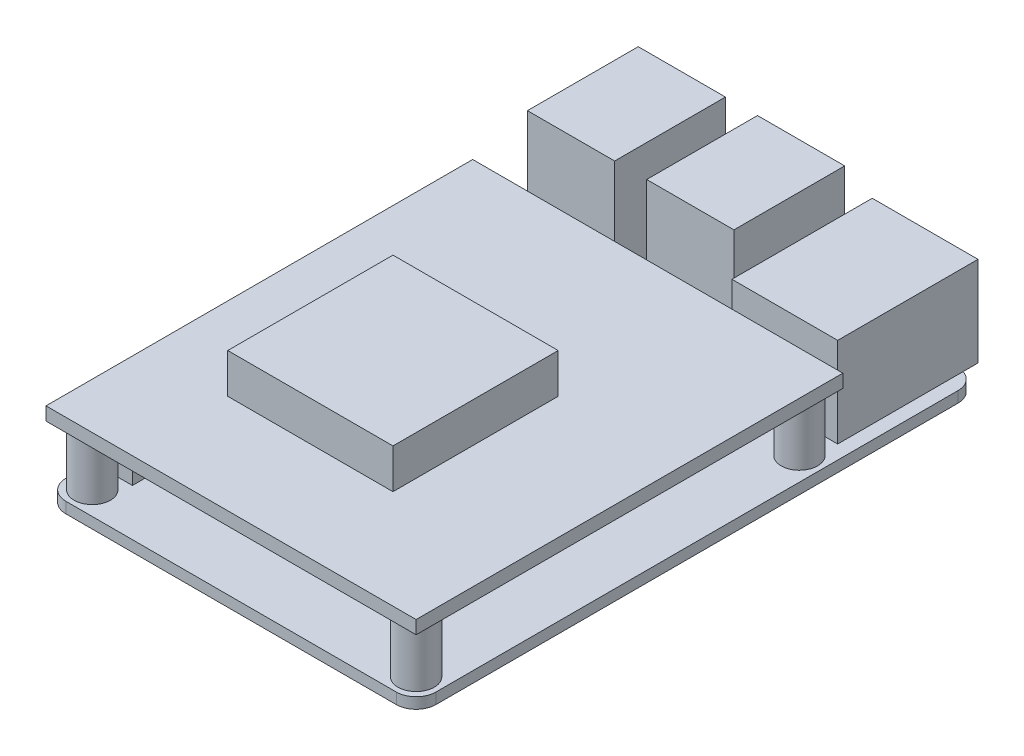
SolidWorks part; units mm, degrees
ref_plane "Front Plane" through (0, 0, 0) normal (0, 0, 1) x (1, 0, 0)
ref_plane "Top Plane" through (0, 0, 0) normal (0, 1, 0) x (1, 0, 0)
ref_plane "Right Plane" through (0, 0, 0) normal (1, 0, 0) x (0, 0, -1)
sketch "Sketch1" plane through (0, 0, 0) normal (0, 1, 0) x (1, 0, 0)
  line L5 (0, -10) -> (0, 0) construction
  line L7 (-24.5, -39) -> (24.5, -39) construction
  line L8 (-24.5, -39) -> (-24.5, 19) construction
  line L13 (-24.5, 19) -> (24.5, 19) construction
  line L14 (24.5, -39) -> (24.5, 19) construction
  line L15 (-24.5, -39) -> (24.5, 19) construction
  line L22 (-24.5, 19) -> (24.5, -39) construction
  line L23 (-25, -42.5) -> (25, -42.5)
  line L24 (-28, -39.5) -> (-28, 39.5)
  line L25 (-25, 42.5) -> (25, 42.5)
  line L26 (28, -39.5) -> (28, 39.5)
  line L27 (-28, -42.5) -> (28, 42.5) construction
  line L28 (-28, 42.5) -> (28, -42.5) construction
  line L29 (28, 0) -> (-28, 0) construction
  circle A22 centre (24.5, 19) radius 1.75
  circle A23 centre (-24.5, 19) radius 1.75
  circle A24 centre (-24.5, -39) radius 1.75
  circle A25 centre (24.5, -39) radius 1.75
  arc A26 (25, -42.5) -> (28, -39.5) centre (25, -39.5) ccw
  arc A27 (-25, -42.5) -> (-28, -39.5) centre (-25, -39.5) cw
  arc A28 (-28, 39.5) -> (-25, 42.5) centre (-25, 39.5) cw
  arc A29 (25, 42.5) -> (28, 39.5) centre (25, 39.5) cw
  point P2 (0, -10)
  point P14 (0, 0)
  dimension "D1" = 3.5
  dimension "D5" = 3
  dimension "D6" = 85
  dimension "D8" = 23.5
  dimension "D3" = 58
  dimension "D4" = 49
  dimension "D7" = 56
extrude "Boss-Extrude1" add sketch "Sketch1" along normal blind 1.651
sketch "Sketch2" plane through (0, 1.651, 0) normal (0, 1, 0) x (1, 0, 0)
  line L0 (-25.5108, 36.2389) -> (5.7312, 36.2389) construction
  line L1 (-25.5108, 44.6209) -> (-12.3155, 44.6209)
  line L2 (-25.5108, 44.6209) -> (-25.5108, 27.8569)
  line L3 (-25.5108, 27.8569) -> (-12.3155, 27.8569)
  line L4 (-12.3155, 44.6209) -> (-12.3155, 27.8569)
  line L5 (-7.4641, 44.6209) -> (5.7312, 44.6209)
  line L6 (-7.4641, 44.6209) -> (-7.4641, 27.8569)
  line L7 (-7.4641, 27.8569) -> (5.7312, 27.8569)
  line L8 (5.7312, 44.6209) -> (5.7312, 27.8569)
  line L9 (-28, 39.5) -> (-28, -39.5) construction
  line L11 (25, 42.5) -> (-25, 42.5) construction
  dimension "D1" = 13.1953
  dimension "D2" = 16.764
  dimension "D3" = 4.8514
  dimension "D4" = 2.4892
  dimension "D5" = 2.1209
extrude "Boss-Extrude2" add sketch "Sketch2" along normal blind 15.748
sketch "Sketch4" plane through (0, 1.651, 0) normal (0, 1, 0) x (1, 0, 0)
  line L0 (5.7312, 44.6209) -> (-7.4641, 44.6209) construction
  line L1 (9.8968, 44.6209) -> (25.8988, 44.6209)
  line L2 (9.8968, 44.6209) -> (9.8968, 23.389)
  line L3 (9.8968, 23.389) -> (25.8988, 23.389)
  line L4 (25.8988, 44.6209) -> (25.8988, 23.389)
  line L5 (5.7312, 27.8569) -> (5.7312, 44.6209) construction
  dimension "D1" = 16.002
  dimension "D2" = 21.2319
  dimension "D3" = 4.1656
extrude "Boss-Extrude3" add sketch "Sketch4" along normal blind 13.589
sketch "Sketch3" plane through (0, 0, -44.6209) normal (0, 0, -1) x (-1, 0, 0)
  line L0 (12.3155, 1.651) -> (25.5108, 1.651) construction
  line L1 (25.5108, 1.651) -> (25.5108, 17.399) construction
  line L2 (25.5108, 17.399) -> (12.3155, 17.399) construction
  line L3 (12.3155, 17.399) -> (12.3155, 1.651) construction
  line L4 (-5.7312, 1.651) -> (7.4641, 1.651) construction
  line L5 (7.4641, 1.651) -> (7.4641, 17.399) construction
  line L6 (7.4641, 17.399) -> (-5.7312, 17.399) construction
  line L7 (-5.7312, 17.399) -> (-5.7312, 1.651) construction
  line L8 (12.3155, 1.651) -> (25.5108, 1.651) construction
  line L9 (25.5108, 1.651) -> (25.5108, 17.399) construction
  line L10 (25.5108, 17.399) -> (12.3155, 17.399) construction
  line L11 (12.3155, 17.399) -> (12.3155, 1.651) construction
  line L12 (-5.7312, 1.651) -> (7.4641, 1.651) construction
  line L13 (7.4641, 1.651) -> (7.4641, 17.399) construction
  line L14 (7.4641, 17.399) -> (-5.7312, 17.399) construction
  line L15 (-5.7312, 17.399) -> (-5.7312, 1.651) construction
  line L16 (13.5855, 2.921) -> (24.2408, 2.921)
  line L17 (24.2408, 2.921) -> (24.2408, 8.89)
  line L18 (24.2408, 16.129) -> (13.5855, 16.129)
  line L19 (13.5855, 16.129) -> (13.5855, 10.16)
  line L20 (-4.4612, 2.921) -> (6.1941, 2.921)
  line L21 (6.1941, 2.921) -> (6.1941, 8.89)
  line L22 (6.1941, 16.129) -> (-4.4612, 16.129)
  line L23 (-4.4612, 16.129) -> (-4.4612, 10.16)
  line L24 (-24.6288, 2.921) -> (-11.1668, 2.921)
  line L25 (-11.1668, 2.921) -> (-11.1668, 13.97)
  line L26 (-11.1668, 13.97) -> (-24.6288, 13.97)
  line L27 (-24.6288, 13.97) -> (-24.6288, 2.921)
  line L28 (-25.8988, 1.651) -> (-9.8968, 1.651)
  line L29 (-9.8968, 1.651) -> (-9.8968, 15.24)
  line L30 (-9.8968, 15.24) -> (-25.8988, 15.24)
  line L31 (-25.8988, 15.24) -> (-25.8988, 1.651)
  line L32 (-25.8988, 1.651) -> (-9.8968, 1.651) construction
  line L33 (-9.8968, 1.651) -> (-9.8968, 15.24) construction
  line L34 (-9.8968, 15.24) -> (-25.8988, 15.24) construction
  line L35 (-25.8988, 15.24) -> (-25.8988, 1.651) construction
  line L36 (-4.4612, 9.525) -> (6.1941, 9.525) construction
  line L37 (13.5855, 9.525) -> (24.2408, 9.525) construction
  line L38 (-4.4612, 8.89) -> (6.1941, 8.89)
  line L39 (13.5855, 8.89) -> (24.2408, 8.89)
  line L40 (-4.4612, 10.16) -> (6.1941, 10.16)
  line L41 (13.5855, 10.16) -> (24.2408, 10.16)
  line L42 (13.5855, 8.89) -> (13.5855, 2.921)
  line L43 (13.5855, 16.129) -> (13.5855, 2.921) construction
  line L44 (24.2408, 10.16) -> (24.2408, 16.129)
  line L45 (24.2408, 2.921) -> (24.2408, 16.129) construction
  line L46 (6.1941, 10.16) -> (6.1941, 16.129)
  line L47 (6.1941, 2.921) -> (6.1941, 16.129) construction
  line L48 (-4.4612, 8.89) -> (-4.4612, 2.921)
  line L49 (-4.4612, 16.129) -> (-4.4612, 2.921) construction
  dimension "D1" = 1.27
  dimension "D2" = 0
  dimension "D3" = 1.27
  dimension "D4" = 0.635
  dimension "D5" = 0.635
extrude "Cut-Extrude1" cut sketch "Sketch3" against normal blind 15.748
sketch "Sketch5" plane through (0, 1.651, 0) normal (0, 1, 0) x (1, 0, 0)
  line L0 (-24.5, 19) -> (-24.5, 15.4) construction
  line L1 (-26.9765, 15.4) -> (-22.0235, 15.4)
  line L2 (-26.9765, 15.4) -> (-26.9765, -35.4)
  line L3 (-26.9765, -35.4) -> (-22.0235, -35.4)
  line L4 (-22.0235, 15.4) -> (-22.0235, -35.4)
  line L5 (-24.5, -39) -> (-24.5, -35.4) construction
  dimension "D1" = 50.8
  dimension "D2" = 4.953
extrude "Boss-Extrude4" add sketch "Sketch5" along normal blind 2.4892
sketch "Sketch6" plane through (0, 4.1402, 0) normal (0, 1, 0) x (1, 0, 0)
  line L0 (-25.8081, 13.9077) -> (-23.1919, 13.9077) construction
  line L3 (-24.5, 15.4) -> (-24.5, -35.4) construction
  line L4 (-26.1065, 13.6093) -> (-25.5096, 13.6093)
  line L5 (-26.1065, 13.6093) -> (-26.1065, 14.2062)
  line L6 (-26.1065, 14.2062) -> (-25.5096, 14.2062)
  line L7 (-25.5096, 13.6093) -> (-25.5096, 14.2062)
  line L8 (-26.1065, 13.6093) -> (-25.5096, 14.2062) construction
  line L9 (-26.1065, 14.2062) -> (-25.5096, 13.6093) construction
  line L10 (-23.4903, 13.6093) -> (-22.8934, 13.6093)
  line L11 (-23.4903, 13.6093) -> (-23.4903, 14.2062)
  line L12 (-23.4903, 14.2062) -> (-22.8934, 14.2062)
  line L13 (-22.8934, 13.6093) -> (-22.8934, 14.2062)
  line L14 (-23.4903, 13.6093) -> (-22.8934, 14.2062) construction
  line L15 (-23.4903, 14.2062) -> (-22.8934, 13.6093) construction
  line L16 (-22.0235, 15.4) -> (-26.9765, 15.4) construction
  line L17 (-26.9765, -35.4) -> (-22.0235, -35.4) construction
  line L18 (-26.1065, 11.0693) -> (-25.5096, 11.0693)
  line L19 (-26.1065, 11.0693) -> (-26.1065, 11.6662)
  line L20 (-25.5096, 11.0693) -> (-25.5096, 11.6662)
  line L21 (-26.1065, 11.6662) -> (-25.5096, 11.6662)
  line L22 (-25.8081, 11.3677) -> (-23.1919, 11.3677) construction
  line L23 (-23.4903, 11.0693) -> (-23.4903, 11.6662)
  line L24 (-23.4903, 11.6662) -> (-22.8934, 11.6662)
  line L25 (-22.8934, 11.0693) -> (-22.8934, 11.6662)
  line L26 (-23.4903, 11.0693) -> (-22.8934, 11.0693)
  line L27 (-26.1065, 8.5293) -> (-25.5096, 8.5293)
  line L28 (-26.1065, 8.5293) -> (-26.1065, 9.1262)
  line L29 (-25.5096, 8.5293) -> (-25.5096, 9.1262)
  line L30 (-26.1065, 9.1262) -> (-25.5096, 9.1262)
  line L31 (-25.8081, 8.8277) -> (-23.1919, 8.8277) construction
  line L32 (-23.4903, 8.5293) -> (-23.4903, 9.1262)
  line L33 (-23.4903, 9.1262) -> (-22.8934, 9.1262)
  line L34 (-22.8934, 8.5293) -> (-22.8934, 9.1262)
  line L35 (-23.4903, 8.5293) -> (-22.8934, 8.5293)
  line L36 (-26.1065, 5.9893) -> (-25.5096, 5.9893)
  line L37 (-26.1065, 5.9893) -> (-26.1065, 6.5862)
  line L38 (-25.5096, 5.9893) -> (-25.5096, 6.5862)
  line L39 (-26.1065, 6.5862) -> (-25.5096, 6.5862)
  line L40 (-25.8081, 6.2877) -> (-23.1919, 6.2877) construction
  line L41 (-23.4903, 5.9893) -> (-23.4903, 6.5862)
  line L42 (-23.4903, 6.5862) -> (-22.8934, 6.5862)
  line L43 (-22.8934, 5.9893) -> (-22.8934, 6.5862)
  line L44 (-23.4903, 5.9893) -> (-22.8934, 5.9893)
  line L45 (-26.1065, 3.4493) -> (-25.5096, 3.4493)
  line L46 (-26.1065, 3.4493) -> (-26.1065, 4.0462)
  line L47 (-25.5096, 3.4493) -> (-25.5096, 4.0462)
  line L48 (-26.1065, 4.0462) -> (-25.5096, 4.0462)
  line L49 (-25.8081, 3.7477) -> (-23.1919, 3.7477) construction
  line L50 (-23.4903, 3.4493) -> (-23.4903, 4.0462)
  line L51 (-23.4903, 4.0462) -> (-22.8934, 4.0462)
  line L52 (-22.8934, 3.4493) -> (-22.8934, 4.0462)
  line L53 (-23.4903, 3.4493) -> (-22.8934, 3.4493)
  line L54 (-26.1065, 0.9093) -> (-25.5096, 0.9093)
  line L55 (-26.1065, 0.9093) -> (-26.1065, 1.5062)
  line L56 (-25.5096, 0.9093) -> (-25.5096, 1.5062)
  line L57 (-26.1065, 1.5062) -> (-25.5096, 1.5062)
  line L58 (-25.8081, 1.2077) -> (-23.1919, 1.2077) construction
  line L59 (-23.4903, 0.9093) -> (-23.4903, 1.5062)
  line L60 (-23.4903, 1.5062) -> (-22.8934, 1.5062)
  line L61 (-22.8934, 0.9093) -> (-22.8934, 1.5062)
  line L62 (-23.4903, 0.9093) -> (-22.8934, 0.9093)
  line L63 (-26.1065, -1.6307) -> (-25.5096, -1.6307)
  line L64 (-26.1065, -1.6307) -> (-26.1065, -1.0338)
  line L65 (-25.5096, -1.6307) -> (-25.5096, -1.0338)
  line L66 (-26.1065, -1.0338) -> (-25.5096, -1.0338)
  line L67 (-25.8081, -1.3323) -> (-23.1919, -1.3323) construction
  line L68 (-23.4903, -1.6307) -> (-23.4903, -1.0338)
  line L69 (-23.4903, -1.0338) -> (-22.8934, -1.0338)
  line L70 (-22.8934, -1.6307) -> (-22.8934, -1.0338)
  line L71 (-23.4903, -1.6307) -> (-22.8934, -1.6307)
  line L72 (-26.1065, -4.1707) -> (-25.5096, -4.1707)
  line L73 (-26.1065, -4.1707) -> (-26.1065, -3.5738)
  line L74 (-25.5096, -4.1707) -> (-25.5096, -3.5738)
  line L75 (-26.1065, -3.5738) -> (-25.5096, -3.5738)
  line L76 (-25.8081, -3.8723) -> (-23.1919, -3.8723) construction
  line L77 (-23.4903, -4.1707) -> (-23.4903, -3.5738)
  line L78 (-23.4903, -3.5738) -> (-22.8934, -3.5738)
  line L79 (-22.8934, -4.1707) -> (-22.8934, -3.5738)
  line L80 (-23.4903, -4.1707) -> (-22.8934, -4.1707)
  line L81 (-26.1065, -6.7107) -> (-25.5096, -6.7107)
  line L82 (-26.1065, -6.7107) -> (-26.1065, -6.1138)
  line L83 (-25.5096, -6.7107) -> (-25.5096, -6.1138)
  line L84 (-26.1065, -6.1138) -> (-25.5096, -6.1138)
  line L85 (-25.8081, -6.4123) -> (-23.1919, -6.4123) construction
  line L86 (-23.4903, -6.7107) -> (-23.4903, -6.1138)
  line L87 (-23.4903, -6.1138) -> (-22.8934, -6.1138)
  line L88 (-22.8934, -6.7107) -> (-22.8934, -6.1138)
  line L89 (-23.4903, -6.7107) -> (-22.8934, -6.7107)
  line L90 (-26.1065, -9.2507) -> (-25.5096, -9.2507)
  line L91 (-26.1065, -9.2507) -> (-26.1065, -8.6538)
  line L92 (-25.5096, -9.2507) -> (-25.5096, -8.6538)
  line L93 (-26.1065, -8.6538) -> (-25.5096, -8.6538)
  line L94 (-25.8081, -8.9523) -> (-23.1919, -8.9523) construction
  line L95 (-23.4903, -9.2507) -> (-23.4903, -8.6538)
  line L96 (-23.4903, -8.6538) -> (-22.8934, -8.6538)
  line L97 (-22.8934, -9.2507) -> (-22.8934, -8.6538)
  line L98 (-23.4903, -9.2507) -> (-22.8934, -9.2507)
  line L99 (-26.1065, -11.7907) -> (-25.5096, -11.7907)
  line L100 (-26.1065, -11.7907) -> (-26.1065, -11.1938)
  line L101 (-25.5096, -11.7907) -> (-25.5096, -11.1938)
  line L102 (-26.1065, -11.1938) -> (-25.5096, -11.1938)
  line L103 (-25.8081, -11.4923) -> (-23.1919, -11.4923) construction
  line L104 (-23.4903, -11.7907) -> (-23.4903, -11.1938)
  line L105 (-23.4903, -11.1938) -> (-22.8934, -11.1938)
  line L106 (-22.8934, -11.7907) -> (-22.8934, -11.1938)
  line L107 (-23.4903, -11.7907) -> (-22.8934, -11.7907)
  line L108 (-26.1065, -14.3307) -> (-25.5096, -14.3307)
  line L109 (-26.1065, -14.3307) -> (-26.1065, -13.7338)
  line L110 (-25.5096, -14.3307) -> (-25.5096, -13.7338)
  line L111 (-26.1065, -13.7338) -> (-25.5096, -13.7338)
  line L112 (-25.8081, -14.0323) -> (-23.1919, -14.0323) construction
  line L113 (-23.4903, -14.3307) -> (-23.4903, -13.7338)
  line L114 (-23.4903, -13.7338) -> (-22.8934, -13.7338)
  line L115 (-22.8934, -14.3307) -> (-22.8934, -13.7338)
  line L116 (-23.4903, -14.3307) -> (-22.8934, -14.3307)
  line L117 (-26.1065, -16.8707) -> (-25.5096, -16.8707)
  line L118 (-26.1065, -16.8707) -> (-26.1065, -16.2738)
  line L119 (-25.5096, -16.8707) -> (-25.5096, -16.2738)
  line L120 (-26.1065, -16.2738) -> (-25.5096, -16.2738)
  line L121 (-25.8081, -16.5723) -> (-23.1919, -16.5723) construction
  line L122 (-23.4903, -16.8707) -> (-23.4903, -16.2738)
  line L123 (-23.4903, -16.2738) -> (-22.8934, -16.2738)
  line L124 (-22.8934, -16.8707) -> (-22.8934, -16.2738)
  line L125 (-23.4903, -16.8707) -> (-22.8934, -16.8707)
  line L126 (-26.1065, -19.4107) -> (-25.5096, -19.4107)
  line L127 (-26.1065, -19.4107) -> (-26.1065, -18.8138)
  line L128 (-25.5096, -19.4107) -> (-25.5096, -18.8138)
  line L129 (-26.1065, -18.8138) -> (-25.5096, -18.8138)
  line L130 (-25.8081, -19.1123) -> (-23.1919, -19.1123) construction
  line L131 (-23.4903, -19.4107) -> (-23.4903, -18.8138)
  line L132 (-23.4903, -18.8138) -> (-22.8934, -18.8138)
  line L133 (-22.8934, -19.4107) -> (-22.8934, -18.8138)
  line L134 (-23.4903, -19.4107) -> (-22.8934, -19.4107)
  line L135 (-26.1065, -21.9507) -> (-25.5096, -21.9507)
  line L136 (-26.1065, -21.9507) -> (-26.1065, -21.3538)
  line L137 (-25.5096, -21.9507) -> (-25.5096, -21.3538)
  line L138 (-26.1065, -21.3538) -> (-25.5096, -21.3538)
  line L139 (-25.8081, -21.6523) -> (-23.1919, -21.6523) construction
  line L140 (-23.4903, -21.9507) -> (-23.4903, -21.3538)
  line L141 (-23.4903, -21.3538) -> (-22.8934, -21.3538)
  line L142 (-22.8934, -21.9507) -> (-22.8934, -21.3538)
  line L143 (-23.4903, -21.9507) -> (-22.8934, -21.9507)
  line L144 (-26.1065, -24.4907) -> (-25.5096, -24.4907)
  line L145 (-26.1065, -24.4907) -> (-26.1065, -23.8938)
  line L146 (-25.5096, -24.4907) -> (-25.5096, -23.8938)
  line L147 (-26.1065, -23.8938) -> (-25.5096, -23.8938)
  line L148 (-25.8081, -24.1923) -> (-23.1919, -24.1923) construction
  line L149 (-23.4903, -24.4907) -> (-23.4903, -23.8938)
  line L150 (-23.4903, -23.8938) -> (-22.8934, -23.8938)
  line L151 (-22.8934, -24.4907) -> (-22.8934, -23.8938)
  line L152 (-23.4903, -24.4907) -> (-22.8934, -24.4907)
  line L153 (-26.1065, -27.0307) -> (-25.5096, -27.0307)
  line L154 (-26.1065, -27.0307) -> (-26.1065, -26.4338)
  line L155 (-25.5096, -27.0307) -> (-25.5096, -26.4338)
  line L156 (-26.1065, -26.4338) -> (-25.5096, -26.4338)
  line L157 (-25.8081, -26.7323) -> (-23.1919, -26.7323) construction
  line L158 (-23.4903, -27.0307) -> (-23.4903, -26.4338)
  line L159 (-23.4903, -26.4338) -> (-22.8934, -26.4338)
  line L160 (-22.8934, -27.0307) -> (-22.8934, -26.4338)
  line L161 (-23.4903, -27.0307) -> (-22.8934, -27.0307)
  line L162 (-26.1065, -29.5707) -> (-25.5096, -29.5707)
  line L163 (-26.1065, -29.5707) -> (-26.1065, -28.9738)
  line L164 (-25.5096, -29.5707) -> (-25.5096, -28.9738)
  line L165 (-26.1065, -28.9738) -> (-25.5096, -28.9738)
  line L166 (-25.8081, -29.2723) -> (-23.1919, -29.2723) construction
  line L167 (-23.4903, -29.5707) -> (-23.4903, -28.9738)
  line L168 (-23.4903, -28.9738) -> (-22.8934, -28.9738)
  line L169 (-22.8934, -29.5707) -> (-22.8934, -28.9738)
  line L170 (-23.4903, -29.5707) -> (-22.8934, -29.5707)
  line L171 (-26.1065, -32.1107) -> (-25.5096, -32.1107)
  line L172 (-26.1065, -32.1107) -> (-26.1065, -31.5138)
  line L173 (-25.5096, -32.1107) -> (-25.5096, -31.5138)
  line L174 (-26.1065, -31.5138) -> (-25.5096, -31.5138)
  line L175 (-25.8081, -31.8123) -> (-23.1919, -31.8123) construction
  line L176 (-23.4903, -32.1107) -> (-23.4903, -31.5138)
  line L177 (-23.4903, -31.5138) -> (-22.8934, -31.5138)
  line L178 (-22.8934, -32.1107) -> (-22.8934, -31.5138)
  line L179 (-23.4903, -32.1107) -> (-22.8934, -32.1107)
  line L180 (-26.1065, -34.6507) -> (-25.5096, -34.6507)
  line L181 (-26.1065, -34.6507) -> (-26.1065, -34.0538)
  line L182 (-25.5096, -34.6507) -> (-25.5096, -34.0538)
  line L183 (-26.1065, -34.0538) -> (-25.5096, -34.0538)
  line L184 (-25.8081, -34.3523) -> (-23.1919, -34.3523) construction
  line L185 (-23.4903, -34.6507) -> (-23.4903, -34.0538)
  line L186 (-23.4903, -34.0538) -> (-22.8934, -34.0538)
  line L187 (-22.8934, -34.6507) -> (-22.8934, -34.0538)
  line L188 (-23.4903, -34.6507) -> (-22.8934, -34.6507)
  point P6 (-25.8081, 13.9077)
  point P11 (-23.1919, 13.9077)
  point P18 (-24.5, 13.9077)
  dimension "D1" = 0.5969
  dimension "D2" = 2.0193
  dimension "D3" = 1.1938
  dimension "D4" = 20
extrude "Boss-Extrude5" add sketch "Sketch6" along normal blind 5.8928
sketch "Sketch7" plane through (0, 1.651, 0) normal (0, 1, 0) x (1, 0, 0)
  line L0 (-22.0235, -35.4) -> (-22.0235, 15.4) construction
  line L1 (-10.5173, -8.9466) -> (3.4781, -8.9466)
  line L2 (-10.5173, -8.9466) -> (-10.5173, -22.942)
  line L3 (-10.5173, -22.942) -> (3.4781, -22.942)
  line L4 (3.4781, -8.9466) -> (3.4781, -22.942)
  line L5 (-25, -42.5) -> (25, -42.5) construction
  dimension "D1" = 13.9954
  dimension "D2" = 11.5062
  dimension "D3" = 19.558
extrude "Boss-Extrude6" add sketch "Sketch7" along normal blind 2.54
sketch "Sketch9" plane through (0, 1.651, 0) normal (0, 1, 0) x (1, 0, 0)
  line L0 (-28, -39.5) -> (-28, 39.5) construction
  line L1 (-28, 22.133) -> (28, 22.133)
  line L2 (-28, 22.133) -> (-28, -42.5)
  line L3 (-28, -42.5) -> (28, -42.5)
  line L4 (28, 22.133) -> (28, -42.5)
  circle A0 centre (-24.5, 19) radius 1.75
  circle A1 centre (24.5, 19) radius 1.75
  circle A2 centre (24.5, -39) radius 1.75
  circle A3 centre (-24.5, -39) radius 1.75
  circle A4 centre (-24.5, -39) radius 2.75
  circle A5 centre (-24.5, 19) radius 2.75
  circle A6 centre (24.5, 19) radius 2.75
  circle A7 centre (24.5, -39) radius 2.75
  circle M5 centre (-24.5, -39) radius 1.75
  circle M6 centre (24.5, 19) radius 1.75
  circle M7 centre (-24.5, 19) radius 1.75
  circle M8 centre (24.5, -39) radius 1.75
  dimension "D1" = 1
extrude "Boss-Extrude7" add sketch "Sketch9" along normal blind 11 contours A4 M5 | A7 M8 | A6 M6 | A5 M7
sketch "Sketch10" plane through (0, 12.651, 0) normal (0, 1, 0) x (1, 0, 0)
  line L1 (-15.5, -27.5) -> (9.5, -27.5)
  line L2 (-15.5, -27.5) -> (-15.5, -2.5)
  line L3 (-15.5, -2.5) -> (9.5, -2.5)
  line L4 (9.5, -27.5) -> (9.5, -2.5)
  line L6 (-25, -42.5) -> (25, -42.5) construction
  line L7 (-28, -39.5) -> (-28, 39.5) construction
  dimension "D1" = 15
  dimension "D2" = 12.5
  dimension "D3" = 25
  dimension "D4" = 25
extrude "Boss-Extrude8" add sketch "Sketch10" along normal blind 6
sketch "Sketch11" plane through (0, 12.651, 0) normal (0, 1, 0) x (1, 0, 0)
  line L0 (-28, -39.5) -> (-28, 39.5) construction
  line L1 (28, -42.5) -> (-28, -42.5)
  line L2 (28, -42.5) -> (28, 22.0628)
  line L3 (28, 22.0628) -> (-28, 22.0628)
  line L4 (-28, -42.5) -> (-28, 22.0628)
extrude "Boss-Extrude9" add sketch "Sketch11" against normal blind 2
